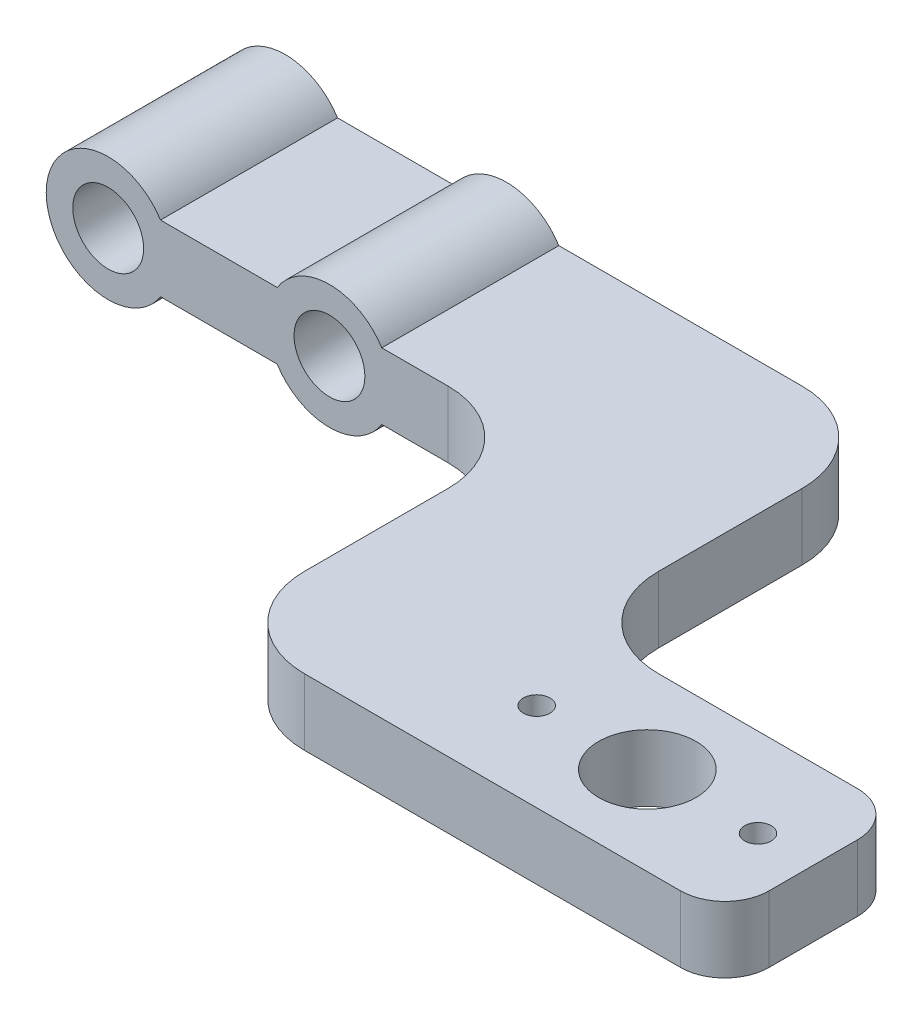
SolidWorks part; units mm, degrees
ref_plane "前视基准面" through (0, 0, 0) normal (0, 0, 1) x (1, 0, 0)
ref_plane "上视基准面" through (0, 0, 0) normal (0, 1, 0) x (1, 0, 0)
ref_plane "右视基准面" through (0, 0, 0) normal (1, 0, 0) x (0, 0, -1)
other "Configuration Table"
sketch "草图1" plane through (0, 0, 0) normal (0, 1, 0) x (1, 0, 0)
  line L0 (9.4005, 0) -> (-11.3027, 0) construction
  line L1 (-7.5, -4) -> (7.5, -4)
  line L2 (-7.5, -4) -> (-7.5, 4)
  line L3 (-7.5, 4) -> (7.5, 4)
  line L4 (7.5, -4) -> (7.5, 4)
  line L5 (-7.5, -4) -> (7.5, 4) construction
  line L6 (-7.5, 4) -> (7.5, -4) construction
  line L7 (0, -8.5148) -> (0, 8.1313) construction
  circle A0 centre (0, 0) radius 2.2
  circle A1 centre (-5, 0) radius 0.6
  circle A2 centre (5, 0) radius 0.6
  point P0 (0, 0)
  dimension "D3" = 4.4
  dimension "D4" = 1.2
  dimension "D5" = 10
  dimension "D1" = 8
  dimension "D2" = 15
extrude "凸台-拉伸1" add sketch "草图1" along normal blind 3
fillet "圆角1" radius 2 2 edges at (7.5, 1.5, -4) (7.5, 1.5, 4)
sketch "草图2" plane through (0, 0, 4) normal (0, 0, 1) x (1, 0, 0)
  line L0 (13.6898, 1.5) -> (-20.3598, 1.5) construction
  line L1 (-7.5, 3) -> (-7.5, 0) construction
  line L2 (-7.5, 0) -> (-7.5, 3)
  line L3 (-7.5, 3) -> (-22.5, 3)
  line L4 (-7.5, 0) -> (-22.5, 0)
  line L5 (-27.2286, 3) -> (-32.5, 3)
  line L6 (-27.2286, 0) -> (-32.5, 0)
  arc A0 (-27.2286, 0) -> (-22.5, 0) centre (-24.8643, 1.5) ccw
  circle A1 centre (-24.8643, 1.5) radius 1.6
  circle A2 centre (-34.8643, 1.5) radius 1.6
  arc A3 (-32.5, 3) -> (-32.5, 0) centre (-34.8643, 1.5) ccw
  arc A4 (-22.5, 3) -> (-27.2286, 3) centre (-24.8643, 1.5) ccw
  point P4 (-7.5, 1.5)
  dimension "D1" = 3.2
  dimension "D2" = 5.6
  dimension "D3" = 3.2
  dimension "D4" = 5.6
  dimension "D5" = 10
  dimension "D6" = 15
extrude "凸台-拉伸2" add sketch "草图2" against normal blind 22.5
sketch "草图3" plane through (0, 3, 0) normal (0, 1, 0) x (1, 0, 0)
  line L0 (-37.6643, 10.5) -> (-15.5, 10.5)
  line L1 (-37.6643, 18.5) -> (-37.6643, -4) construction
  line L2 (-15.5, 10.5) -> (-15.5, -4)
  line L3 (-22.5, -4) -> (5.5, -4) construction
  line L4 (-15.5, -4) -> (-37.6643, -4)
  line L5 (-37.6643, -4) -> (-37.6643, 10.5)
  line L6 (-7.5, 18.5) -> (-22.5, 18.5) construction
  line L7 (-7.5, 18.5) -> (-7.5, 4) construction
  dimension "D1" = 8
  dimension "D2" = 8
extrude "切除-拉伸1" cut sketch "草图3" against normal through all both and the other way through all
fillet "圆角2" radius 4 4 edges at (-15.5, 1.5, -10.5) (-7.5, 1.5, -18.5) (-7.5, 1.5, -4) (-15.5, 1.5, 4)
